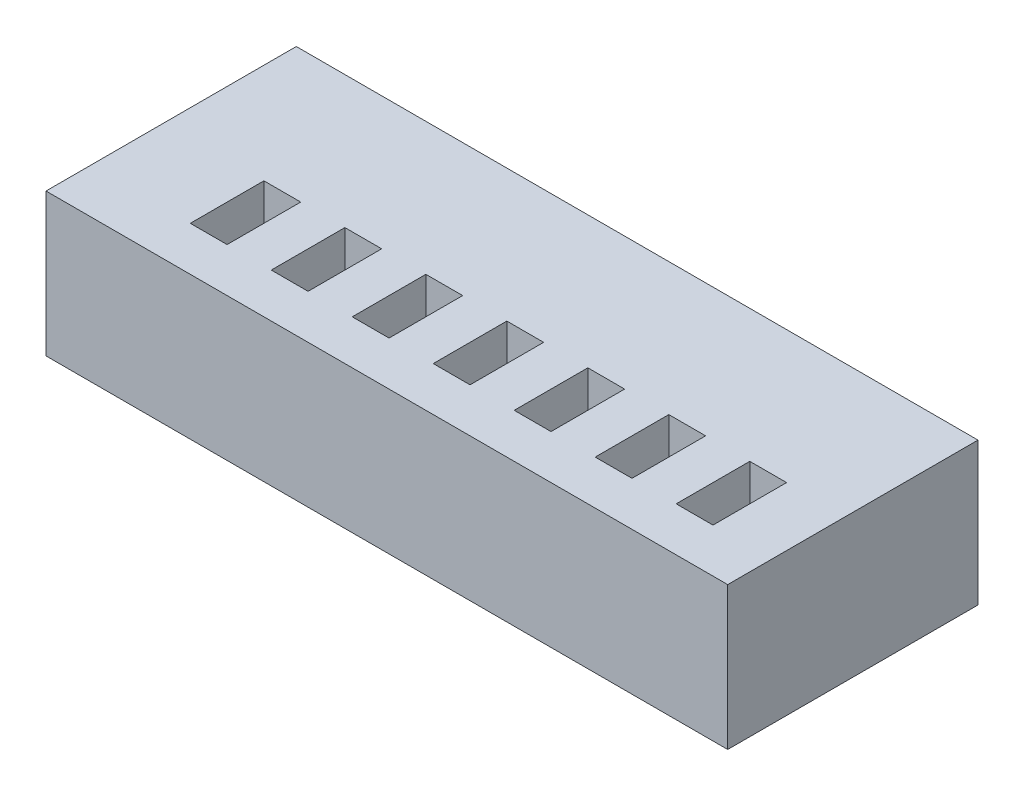
SolidWorks part; units mm, degrees
ref_plane "Front Plane" through (0, 0, 0) normal (0, 0, 1) x (1, 0, 0)
ref_plane "Top Plane" through (0, 0, 0) normal (0, 1, 0) x (1, 0, 0)
ref_plane "Right Plane" through (0, 0, 0) normal (1, 0, 0) x (0, 0, -1)
sketch "Sketch1" plane through (0, 0, 0) normal (0, 1, 0) x (1, 0, 0)
  line L1 (-58.801, -21.59) -> (58.801, -21.59)
  line L2 (-58.801, -21.59) -> (-58.801, 21.59)
  line L3 (-58.801, 21.59) -> (58.801, 21.59)
  line L4 (58.801, -21.59) -> (58.801, 21.59)
  line L5 (-58.801, -21.59) -> (58.801, 21.59) construction
  line L6 (-58.801, 21.59) -> (58.801, -21.59) construction
  point P0 (0, 0)
  dimension "D1" = 117.602
  dimension "D2" = 43.18
extrude "Boss-Extrude1" add sketch "Sketch1" along normal mid plane 24.638
sketch "Sketch2" plane through (0, 12.319, 0) normal (0, 1, 0) x (1, 0, 0)
  line L0 (-58.801, -21.59) -> (58.801, -21.59) construction
  line L1 (42.291, -1.27) -> (48.641, -1.27)
  line L2 (42.291, -1.27) -> (42.291, -13.97)
  line L3 (42.291, -13.97) -> (48.641, -13.97)
  line L4 (48.641, -1.27) -> (48.641, -13.97)
  line L5 (42.291, -1.27) -> (48.641, -13.97) construction
  line L6 (42.291, -13.97) -> (48.641, -1.27) construction
  line L7 (58.801, -21.59) -> (58.801, 21.59) construction
  line L8 (28.321, -1.27) -> (34.671, -1.27)
  line L9 (28.321, -1.27) -> (28.321, -13.97)
  line L10 (28.321, -13.97) -> (34.671, -13.97)
  line L11 (34.671, -1.27) -> (34.671, -13.97)
  line L12 (28.321, -1.27) -> (34.671, -13.97) construction
  line L13 (28.321, -13.97) -> (34.671, -1.27) construction
  line L14 (14.351, -1.27) -> (20.701, -1.27)
  line L15 (14.351, -1.27) -> (14.351, -13.97)
  line L16 (14.351, -13.97) -> (20.701, -13.97)
  line L17 (20.701, -1.27) -> (20.701, -13.97)
  line L18 (14.351, -1.27) -> (20.701, -13.97) construction
  line L19 (14.351, -13.97) -> (20.701, -1.27) construction
  line L20 (0.381, -1.27) -> (6.731, -1.27)
  line L21 (0.381, -1.27) -> (0.381, -13.97)
  line L22 (0.381, -13.97) -> (6.731, -13.97)
  line L23 (6.731, -1.27) -> (6.731, -13.97)
  line L24 (0.381, -1.27) -> (6.731, -13.97) construction
  line L25 (0.381, -13.97) -> (6.731, -1.27) construction
  line L26 (-13.589, -1.27) -> (-7.239, -1.27)
  line L27 (-13.589, -1.27) -> (-13.589, -13.97)
  line L28 (-13.589, -13.97) -> (-7.239, -13.97)
  line L29 (-7.239, -1.27) -> (-7.239, -13.97)
  line L30 (-13.589, -1.27) -> (-7.239, -13.97) construction
  line L31 (-13.589, -13.97) -> (-7.239, -1.27) construction
  line L32 (-27.559, -1.27) -> (-21.209, -1.27)
  line L33 (-27.559, -1.27) -> (-27.559, -13.97)
  line L34 (-27.559, -13.97) -> (-21.209, -13.97)
  line L35 (-21.209, -1.27) -> (-21.209, -13.97)
  line L36 (-27.559, -1.27) -> (-21.209, -13.97) construction
  line L37 (-27.559, -13.97) -> (-21.209, -1.27) construction
  line L38 (-41.529, -1.27) -> (-35.179, -1.27)
  line L39 (-41.529, -1.27) -> (-41.529, -13.97)
  line L40 (-41.529, -13.97) -> (-35.179, -13.97)
  line L41 (-35.179, -1.27) -> (-35.179, -13.97)
  line L42 (-41.529, -1.27) -> (-35.179, -13.97) construction
  line L43 (-41.529, -13.97) -> (-35.179, -1.27) construction
  point P0 (45.466, -7.62)
  point P10 (31.496, -7.62)
  point P15 (17.526, -7.62)
  point P20 (3.556, -7.62)
  point P25 (-10.414, -7.62)
  point P30 (-24.384, -7.62)
  point P35 (-38.354, -7.62)
  dimension "D1" = 6.35
  dimension "D2" = 12.7
  dimension "D3" = 7.62
  dimension "D4" = 10.16
  dimension "D5" = 7
extrude "Cut-Extrude1" cut sketch "Sketch2" against normal blind 12.7
sketch "Sketch3" plane through (-58.801, 0, 0) normal (-1, 0, 0) x (0, 0, 1)
  line L1 (-15.1403, -3.7971) -> (15.1403, -3.7971)
  line L2 (-15.1403, -3.7971) -> (-15.1403, 3.7971)
  line L3 (-15.1403, 3.7971) -> (15.1403, 3.7971)
  line L4 (15.1403, -3.7971) -> (15.1403, 3.7971)
  line L5 (-15.1403, -3.7971) -> (15.1403, 3.7971) construction
  line L6 (-15.1403, 3.7971) -> (15.1403, -3.7971) construction
  point P0 (0, 0)
extrude "Cut-Extrude2" cut sketch "Sketch3" against normal blind 12.7
